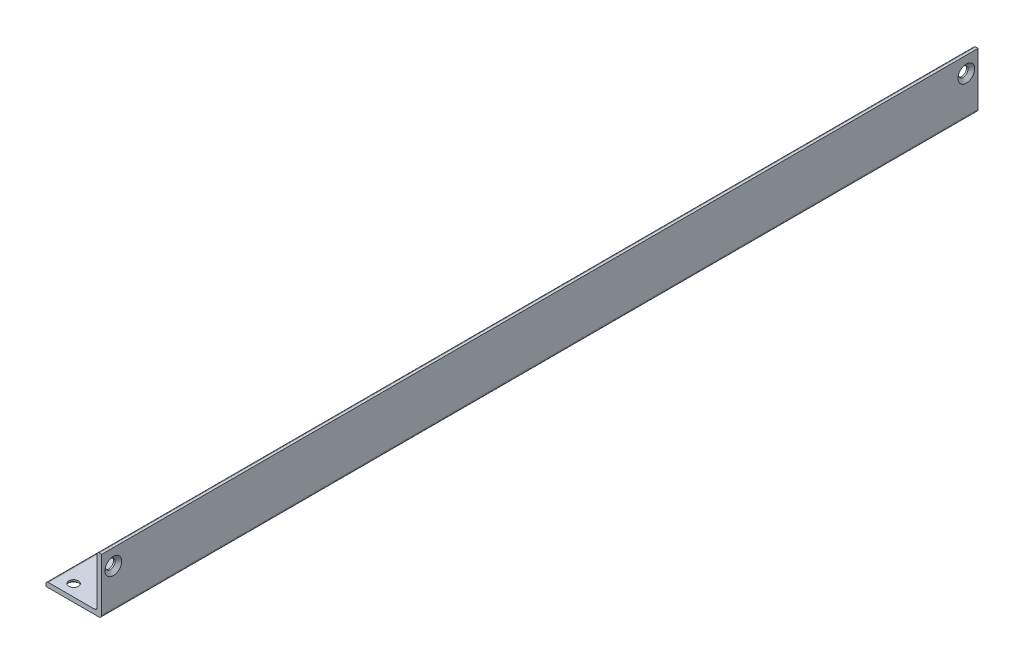
SolidWorks part; units mm, degrees
material "6061-T6 (SS)"
ref_plane "Front Plane" through (0, 0, 0) normal (0, 0, 1) x (1, 0, 0)
ref_plane "Top Plane" through (0, 0, 0) normal (0, 1, 0) x (1, 0, 0)
ref_plane "Right Plane" through (0, 0, 0) normal (1, 0, 0) x (0, 0, -1)
sketch "Sketch2" plane through (0, 0, 0) normal (0, 0, 1) x (1, 0, 0)
  line L0 (-9.525, 0) -> (9.525, 0)
  line L1 (9.525, 0) -> (9.525, 19.05)
  line L2 (9.525, 19.05) -> (7.9375, 19.05) construction
  line L3 (7.9375, 18.2563) -> (7.9375, 2.3812)
  line L4 (7.1438, 1.5875) -> (-8.7313, 1.5875)
  line L5 (-9.525, 0) -> (-9.525, 1.5875) construction
  line L6 (8.7313, 19.05) -> (9.525, 19.05)
  line L7 (-9.525, 0.7937) -> (-9.525, 0)
  arc A0 (7.9375, 18.2563) -> (8.7313, 19.05) centre (8.7313, 18.2563) cw
  arc A1 (-9.525, 0.7937) -> (-8.7313, 1.5875) centre (-8.7313, 0.7937) cw
  arc A2 (7.9375, 2.3812) -> (7.1438, 1.5875) centre (7.1438, 2.3812) cw
  dimension "Vert" = 19.05
  dimension "Horz" = 19.05
  dimension "Thickness" = 1.5875
extrude "Boss-Extrude1" add sketch "Sketch2" along normal mid plane 300
ref_plane "Contact Plane 1" through (0, 1.5875, 0) normal (0, 1, 0) x (1, 0, 0)
ref_plane "Contact Plane 2" through (7.9375, 0, 0) normal (-1, 0, 0) x (0, 0, 1)
sketch "Sketch6" plane through (0, 0, 0) normal (0, -1, 0) x (1, 0, 0)
  line L0 (9.525, 146) -> (-4.0625, 146) construction
  line L1 (9.525, 150) -> (9.525, -150) construction
  line L2 (-9.525, 150) -> (9.525, 150) construction
  line L3 (9.525, 0) -> (-9.525, 0) construction
  line L4 (-9.525, 150) -> (-9.525, -150) construction
  point P7 (-4.0625, 146)
  point P11 (-4.0625, -146)
  dimension "D1" = 4
  dimension "D2" = 13.5875
hole_wizard "CSK for #4 Flat Head Machine Screw (100)1" positions "Sketch7" profile "Sketch8" countersink size "#4" standard "ANSI Inch" end condition through all
sketch "Sketch7" plane through (0, 0, 0) normal (0, -1, 0) x (-1, 0, 0)
  point P0 (4.0625, -146)
  point P3 (4.0625, 146)
sketch "Sketch8" plane through (-4.0625, 0, 146) normal (1, 0, 0) x (0, 0, -1)
  line L0 (0, 0) -> (0, 19.05)
  line L1 (0, 19.05) -> (1.6319, 19.05)
  line L2 (1.6319, 19.05) -> (1.6319, 1.0284)
  line L3 (1.6319, 1.0284) -> (2.8575, 0)
  line L5 (2.8575, 0) -> (0, 0)
  line L6 (-1.6319, 1.0284) -> (-2.8575, 0) construction
  line L11 (0, -6.35) -> (0, 107.95) construction
  dimension "Thru Hole Dia." = 3.2639
  dimension "Thru Hole Depth" = 19.05
  dimension "Near C'Sink Dia." = 5.715
  dimension "Near C'Sink Angle" = 100
sketch "Sketch9" plane through (9.525, 0, 0) normal (1, 0, 0) x (0, 0, -1)
  line L0 (-146, 0) -> (-146, 13.5875) construction
  line L1 (0, 0) -> (0, 19.05) construction
  line L2 (-150, 0) -> (150, 0) construction
  line L3 (-150, 19.05) -> (150, 19.05) construction
  point P4 (-146, 13.5875)
  point P10 (146, 13.5875)
  dimension "D1" = 13.5875
hole_wizard "CSK for #4 Flat Head Machine Screw (100)2" positions "Sketch10" profile "Sketch11" countersink size "#4" standard "ANSI Inch" end condition through all
sketch "Sketch10" plane through (9.525, 0, 0) normal (1, 0, 0) x (0, 0, -1)
  point P0 (-146, 13.5875)
  point P3 (146, 13.5875)
sketch "Sketch11" plane through (9.525, 13.5875, 146) normal (0, 1, 0) x (0, 0, -1)
  line L0 (0, 0) -> (0, 19.05)
  line L1 (0, 19.05) -> (1.6319, 19.05)
  line L2 (1.6319, 19.05) -> (1.6319, 1.0284)
  line L3 (1.6319, 1.0284) -> (2.8575, 0)
  line L5 (2.8575, 0) -> (0, 0)
  line L6 (-1.6319, 1.0284) -> (-2.8575, 0) construction
  line L11 (0, -6.35) -> (0, 107.95) construction
  dimension "Thru Hole Dia." = 3.2639
  dimension "Thru Hole Depth" = 19.05
  dimension "Near C'Sink Dia." = 5.715
  dimension "Near C'Sink Angle" = 100
fillet "Fillet1" radius 1 1 edges at (9.525, 0, 0)
sketch "Sketch27" plane through (0, 1.5875, 0) normal (0, 1, 0) x (1, 0, 0)
  line L0 (7.1438, -150) -> (7.1438, 150) construction
  line L1 (7.1438, -150) -> (-8.7313, -150) construction
  point P0 (3.4938, -129.88)
  point P1 (3.4937, -125.08)
  dimension "D1" = 4.8
  dimension "D2" = 3.65
  dimension "D3" = 20.12
hole_wizard "#2 Clearance Hole1" positions "Sketch28" profile "Sketch30" hole size "#2" standard "ANSI Inch" end condition through all
sketch "Sketch28" plane through (0, 1.5875, 0) normal (0, 1, 0) x (1, 0, 0)
  point P0 (3.4938, -129.88)
  point P3 (3.4937, -125.08)
sketch "Sketch30" plane through (3.4938, 1.5875, 129.88) normal (1, 0, 0) x (0, 0, 1)
  line L0 (0, 0) -> (0, 1.5875)
  line L1 (0, 1.5875) -> (2.0574, 1.5875)
  line L2 (1.2192, 0.6233) -> (1.2192, 0)
  line L5 (1.2192, 0) -> (0, 0)
  line L7 (2.0574, 1.5875) -> (1.2192, 0.6233)
  line L8 (-2.0574, 1.5875) -> (-1.2192, 0.6233) construction
  line L11 (0, -6.35) -> (0, 107.95) construction
  dimension "Thru Hole Dia." = 2.4384
  dimension "Thru Hole Depth" = 1.5875
  dimension "Far C'Sink Dia." = 4.1148
  dimension "Far C'Sink Angle" = 82
sketch "Sketch15" [suppressed] plane through (9.525, 0, 0) normal (1, 0, 0) x (0, 0, -1)
  line L0 (-96, 13.5875) -> (96, 13.5875) construction
  point P4 (0, 13.5875)
sketch "Sketch16" [suppressed] plane through (0, 0, 0) normal (0, -1, 0) x (1, 0, 0)
  line L0 (-4.0625, 96) -> (-4.0625, -96) construction
  point P4 (-4.0625, 0)
hole_wizard "CSK for #4 Flat Head Machine Screw (100)3" [suppressed] positions "Sketch17" profile "Sketch18" countersink size "#4" standard "ANSI Inch"
sketch "Sketch17" plane through (0, 0, 0) normal (0, -1, 0) x (-1, 0, 0)
  point P0 (4.0625, 0)
sketch "Sketch18" plane through (-4.0625, 0, 0) normal (1, 0, 0) x (0, 0, -1)
  line L0 (0, 0) -> (0, 8.5806)
  line L1 (0, 8.5806) -> (1.6319, 7.6)
  line L2 (1.6319, 7.6) -> (1.6319, 1.0284)
  line L3 (1.6319, 1.0284) -> (2.8575, 0)
  line L5 (2.8575, 0) -> (0, 0)
  line L6 (-1.6319, 1.0284) -> (-2.8575, 0) construction
  line L10 (0, 8.5806) -> (-1.632, 7.6) construction
  line L11 (0, -6.35) -> (0, 107.95) construction
  dimension "Hole Dia." = 3.2639
  dimension "Hole Depth" = 7.6
  dimension "Near C'Sink Dia." = 5.715
  dimension "Near C'Sink Angle" = 100
  dimension "Drill Angle" = 118
hole_wizard "CSK for #4 Flat Head Machine Screw (100)4" [suppressed] positions "Sketch19" profile "Sketch20" countersink size "#4" standard "ANSI Inch"
sketch "Sketch19" plane through (9.525, 0, 0) normal (1, 0, 0) x (0, 0, -1)
  point P0 (0, 13.5875)
sketch "Sketch20" plane through (9.525, 13.5875, 0) normal (0, 1, 0) x (0, 0, -1)
  line L0 (0, 0) -> (0, 8.5806)
  line L1 (0, 8.5806) -> (1.6319, 7.6)
  line L2 (1.6319, 7.6) -> (1.6319, 1.0284)
  line L3 (1.6319, 1.0284) -> (2.8575, 0)
  line L5 (2.8575, 0) -> (0, 0)
  line L6 (-1.6319, 1.0284) -> (-2.8575, 0) construction
  line L10 (0, 8.5806) -> (-1.6319, 7.6) construction
  line L11 (0, -6.35) -> (0, 107.95) construction
  dimension "Hole Dia." = 3.2639
  dimension "Hole Depth" = 7.6
  dimension "Near C'Sink Dia." = 5.715
  dimension "Near C'Sink Angle" = 100
  dimension "Drill Angle" = 118
sketch "Sketch21" [suppressed] plane through (9.525, 0, 0) normal (1, 0, 0) x (0, 0, -1)
  line L0 (-146, 13.5875) -> (-150, 13.5875) construction
  line L1 (-150, 1) -> (-150, 19.05) construction
  line L2 (-150, 13.5875) -> (-50, 13.5875) construction
  line L3 (150, 13.5875) -> (50, 13.5875) construction
  line L4 (150, 1) -> (150, 19.05) construction
  point P11 (-50, 13.5875)
  point P12 (50, 13.5875)
  dimension "D1" = 100
  dimension "D2" = 100
hole_wizard "CSK for #4 Flat Head Machine Screw (100)5" [suppressed] positions "Sketch22" profile "Sketch23" countersink size "#4" standard "ANSI Inch"
sketch "Sketch22" plane through (9.525, 0, 0) normal (1, 0, 0) x (0, 0, -1)
  point P0 (-50, 13.5875)
  point P3 (50, 13.5875)
sketch "Sketch23" plane through (9.525, 13.5875, 50) normal (0, 1, 0) x (0, 0, -1)
  line L0 (0, 0) -> (0, 8.5806)
  line L1 (0, 8.5806) -> (1.6319, 7.6)
  line L2 (1.6319, 7.6) -> (1.6319, 1.0284)
  line L3 (1.6319, 1.0284) -> (2.8575, 0)
  line L5 (2.8575, 0) -> (0, 0)
  line L6 (-1.6319, 1.0284) -> (-2.8575, 0) construction
  line L10 (0, 8.5806) -> (-1.6319, 7.6) construction
  line L11 (0, -6.35) -> (0, 107.95) construction
  dimension "Hole Dia." = 3.2639
  dimension "Hole Depth" = 7.6
  dimension "Near C'Sink Dia." = 5.715
  dimension "Near C'Sink Angle" = 100
  dimension "Drill Angle" = 118
sketch "Sketch24" [suppressed] plane through (0, 0, 0) normal (0, -1, 0) x (1, 0, 0)
  line L0 (-4.0625, 146) -> (-4.0625, 150) construction
  line L1 (-9.525, 150) -> (8.525, 150) construction
  line L2 (-4.0625, 150) -> (-4.0625, 50) construction
  line L3 (-4.0625, -150) -> (-4.0625, -50) construction
  line L4 (-9.525, -150) -> (8.525, -150) construction
  point P11 (-4.0625, 50)
  point P12 (-4.0625, -50)
  dimension "D1" = 100
  dimension "D2" = 100
hole_wizard "CSK for #4 Flat Head Machine Screw (100)6" [suppressed] positions "Sketch25" profile "Sketch26" countersink size "#4" standard "ANSI Inch"
sketch "Sketch25" plane through (0, 0, 0) normal (0, -1, 0) x (-1, 0, 0)
  point P0 (4.0625, -50)
  point P3 (4.0625, 50)
sketch "Sketch26" plane through (-4.0625, 0, 50) normal (1, 0, 0) x (0, 0, -1)
  line L0 (0, 0) -> (0, 8.5806)
  line L1 (0, 8.5806) -> (1.6319, 7.6)
  line L2 (1.6319, 7.6) -> (1.6319, 1.0284)
  line L3 (1.6319, 1.0284) -> (2.8575, 0)
  line L5 (2.8575, 0) -> (0, 0)
  line L6 (-1.6319, 1.0284) -> (-2.8575, 0) construction
  line L10 (0, 8.5806) -> (-1.6319, 7.6) construction
  line L11 (0, -6.35) -> (0, 107.95) construction
  dimension "Hole Dia." = 3.2639
  dimension "Hole Depth" = 7.6
  dimension "Near C'Sink Dia." = 5.715
  dimension "Near C'Sink Angle" = 100
  dimension "Drill Angle" = 118
